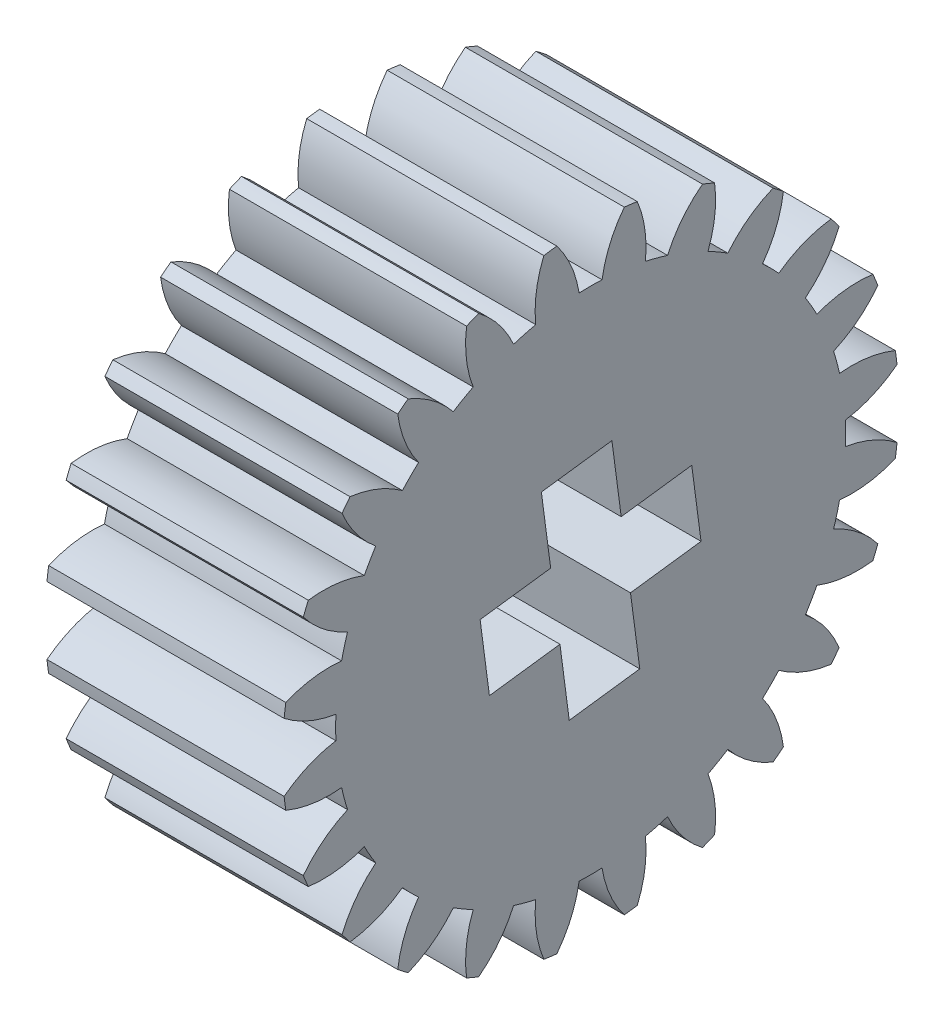
SolidWorks part; units mm, degrees
ref_plane "Plane1" through (0, 0, 0) normal (0, 0, 1) x (1, 0, 0)
ref_plane "Plane2" through (0, 0, 0) normal (0, 1, 0) x (1, 0, 0)
ref_plane "Plane3" through (0, 0, 0) normal (1, 0, 0) x (0, 0, -1)
other "Configuration Table"
sketch "HoldingSke" plane through (0, 0, 0) normal (0, 1, 0) x (1, 0, 0)
  line L0 (0, 0) -> (0.9135, -0.4067)
  line L1 (-15, 0) -> (100, 0) construction
  line L2 (0, 0) -> (-2.1039, 2.3779)
  line L3 (0, 0) -> (-11.863, 4.5341)
  line L4 (0, 0) -> (7.8894, 3.5126)
  line L5 (0, 0) -> (-46.8476, -17.4728)
  line L6 (0, 0) -> (-8.2896, -5.593)
  line L7 (-2.1039, 2.3779) -> (8.6586, 51.2059)
  line L8 (-76.2, 54.61) -> (-76.1, 54.61)
  line L9 (-71.009, 38.7566) -> (-53.1078, 45.2721)
  line L10 (-76.2, 71.12) -> (104.1128, 71.12)
  line L11 (0, 0) -> (-10, 0)
  line L12 (-76.2, 101.6) -> (-76.162, 101.6)
  line L13 (24.9733, 27.94) -> (52.9518, 28.4284)
  line L14 (24.9733, 27.94) -> (24.9743, 27.94)
  line L15 (24.9733, 27.94) -> (100.4006, 29.5858)
  line L16 (-63.627, -1) -> (-12.827, -1)
  circle A0 centre (0, 0) radius 0.5
  circle A1 centre (0, 0) radius 10.749
  circle A2 centre (0, 0) radius 37.5
  circle A3 centre (0, 0) radius 0.5
  dimension "MHD" = 21.498
  dimension "Hub_dia" = 75
  dimension "Bore" = 1
  dimension "MBD" = 1
  dimension "Num_teeth" = 24
  dimension "Pitch" = 1
  dimension "Overall_len" = 50
  dimension "Show_teeth" = 24
  dimension "Thickness" = 10
  dimension "OAL" = 50.0001
  dimension "T_dim" = 0.1
  dimension "Ap" = 20
  dimension "H" = 19.05
  dimension "Pitch_radius" = 180.3128
  dimension "Width" = 10
  dimension "Backlash" = 0.038
  dimension "Addendum_fac" = 1
  dimension "Dedendum_fac" = 1.25
  dimension "Clearance_fac" = 0.25
  dimension "Dedendum_add" = 0.001
  dimension "Module" = 1
sketch "BasProSke" plane through (0, 0, 0) normal (0, 1, 0) x (1, 0, 0)
  line L0 (-10, 0) -> (60, 0) construction
  line L1 (0, 0) -> (0, 13)
  line L2 (0, 0) -> (10, 0)
  line L3 (10, 0) -> (10, 13)
  line L4 (10, 13) -> (0, 13)
  dimension "Thickness" = 10
  dimension "Diameter" = 26
revolve "Base-Revolve" add sketch "BasProSke" angle 360 about L0
sketch "TooCutSke" plane through (0, 0, 0) normal (1, 0, 0) x (0, 0, -1)
  line L1 (0, 0) -> (0, 107) construction
  line L2 (0, 0) -> (-0.8513, 11.9698) construction
  line L3 (0, 0) -> (-3.127, 23.752) construction
  line L4 (-0.8513, 11.9698) -> (-1.5635, 11.876) construction
  arc A0 (0.4834, 10.7381) -> (-0.4834, 10.7381) centre (0, 0) ccw
  arc A1 (1.4409, 12.9455) -> (-1.4409, 12.9455) centre (0, 0) ccw
  circle A2 centre (0, 0) radius 12 construction
  circle A3 centre (0, 0) radius 11.2763 construction
  arc A4 (-0.4834, 10.7381) -> (-1.4409, 12.9455) centre (-5.2252, 9.9926) ccw
  arc A5 (1.4409, 12.9455) -> (0.4834, 10.7381) centre (5.2252, 9.9926) ccw
  dimension "Root_dia" = 21.498
  dimension "Overcut_dia" = 26.0508
  dimension "Pitch_dia" = 24
  dimension "Base_dia" = 22.5526
  dimension "Flank_rad" = 4.8
  dimension "Half_ang" = 7.5
  dimension "Half_CT" = 0.7183
extrude "ToothCut" cut sketch "TooCutSke" along normal through all
fillet "Breaks" [suppressed] radius 0.02
fillet "RootFillets" [suppressed] radius 0.251
pattern_circular "TeethCuts" count 24 every 15 about axis through (-10, 0, 0) along (1, 0, 0) of "ToothCut", "RootFillets", "Breaks"
sketch "HubNeaOneSke" plane through (0, 0, 0) normal (-1, 0, 0) x (0, 0, 1)
  circle A0 centre (0, 0) radius 10.749
  dimension "Diameter" = 21.498
extrude "HubNearOne" [suppressed] add sketch "HubNeaOneSke" along normal blind 40.0001
sketch "HubNeaBotSke" plane through (0, 0, 0) normal (-1, 0, 0) x (0, 0, 1)
  circle A0 centre (0, 0) radius 10.749
  dimension "Diameter" = 21.498
extrude "HubNearBoth" [suppressed] add sketch "HubNeaBotSke" along normal blind 20
ref_plane "FarPln" through (10, 0, 0) normal (1, 0, 0) x (0, 0, -1)
sketch "HubFarSke" plane through (10, 0, 0) normal (1, 0, 0) x (0, 0, -1)
  circle A0 centre (0, 0) radius 10.749
  dimension "Diameter" = 21.498
extrude "HubFar" [suppressed] add sketch "HubFarSke" along normal blind 20
sketch "BorSke" plane through (0, 0, 0) normal (1, 0, 0) x (0, 0, -1)
  circle A0 centre (0, 0) radius 0.5
  dimension "Diameter" = 1
extrude "Bore" cut sketch "BorSke" along normal mid plane 100.0001
sketch "KeySke" plane through (0, 0, 0) normal (1, 0, 0) x (0, 0, -1)
  line L0 (-0.05, 0) -> (-0.05, 0.6)
  line L1 (-0.05, 0.6) -> (0.05, 0.6)
  line L2 (0.05, 0.6) -> (0.05, 0)
  line L3 (0, 0) -> (0, 34) construction
  line L4 (-0.05, 0) -> (0.05, 0)
  dimension "Offset" = 0.6
  dimension "Width" = 0.1
extrude "Keyway" [suppressed] cut sketch "KeySke" along normal mid plane 100.0001
pattern_circular "Keyway2" [suppressed] count 2 every 90 about axis through (-10, 0, 0) along (1, 0, 0)
sketch "Sketch1" plane through (10, 0, 0) normal (1, 0, 0) x (0, 0, -1)
  line L0 (1.6968, -12.8888) -> (-1.6968, 12.8888) construction
  line L1 (-12.8888, -1.6968) -> (12.8888, 1.6968) construction
  line L2 (1.683, -1.2914) -> (4.6573, -0.8998)
  line L3 (-4.2657, -2.0745) -> (-1.2914, -1.683)
  line L4 (-4.2657, -2.0745) -> (-4.6573, 0.8998)
  line L5 (-4.6573, 0.8998) -> (-1.683, 1.2914)
  line L6 (4.6573, -0.8998) -> (4.2657, 2.0745)
  line L7 (2.0745, -4.2657) -> (-0.8998, -4.6573)
  line L8 (2.0745, -4.2657) -> (1.683, -1.2914)
  line L9 (0.8998, 4.6573) -> (-2.0745, 4.2657)
  line L10 (-0.8998, -4.6573) -> (-1.2914, -1.683)
  line L11 (1.2914, 1.683) -> (0.8998, 4.6573)
  line L12 (1.2914, 1.683) -> (4.2657, 2.0745)
  line L13 (-1.683, 1.2914) -> (-2.0745, 4.2657)
  arc A4 (12.9219, 1.4227) -> (12.8498, 1.9702) centre (0, 0) ccw construction
  arc A5 (-12.9219, -1.4227) -> (-12.8498, -1.9702) centre (0, 0) ccw construction
  arc A6 (1.4227, -12.9219) -> (1.9702, -12.8498) centre (0, 0) ccw construction
  arc A7 (-1.4227, 12.9219) -> (-1.9702, 12.8498) centre (0, 0) ccw construction
  point P2 (12.8888, 1.6968)
  point P6 (-12.8888, -1.6968)
  point P12 (1.6968, -12.8888)
  point P16 (0, 0)
  point P25 (-1.6968, 12.8888)
  dimension "D1" = 9
extrude "Cut-Extrude1" cut sketch "Sketch1" against normal through all
equation "' \"Module@HoldingSke\" = 6.35"
equation "' \"Num_teeth@HoldingSke\" = 12"
equation "' \"Ap@HoldingSke\" =  20"
equation "' \"Ap@HoldingSke\" = 20"
equation "' \"Width@HoldingSke\" = 0.5 * 25.4"
equation "' \"Hub_dia@HoldingSke\"= 1 * 25.4"
equation "' \"Hub_dia@HoldingSke\" = 1 * 25.4"
equation "' \"Overall_len@HoldingSke\" = 1.0 * 25.4"
equation "' \"Bore@HoldingSke\" = 0.75 * 25.4"
equation "' \"T_dim@HoldingSke\" = 0.1 * 25.4"
equation "' \"Width@KeySke\" = 0.25 * 25.4"
equation "' \"Show_teeth@HoldingSke\" = 13"
equation "' \"Backlash@HoldingSke\" = 0.009 * 25.4"
equation "' \"Addendum_fac@HoldingSke\" = 1.0"
equation "' \"Dedendum_fac@HoldingSke\" = 1.25"
equation "' \"Dedendum_add@HoldingSke\" = 0.00005 * 25.4"
equation "' \"Clearance_fac@HoldingSke\" = 0.25"
equation "\"Pitch@HoldingSke\" = 1 / \"Module@HoldingSke\""
equation "\"Overcut_dia@TooCutSke\" = (\"Num_teeth@HoldingSke\" + 2 * \"Addendum_fac@HoldingSke\") / \"Pitch@HoldingSke\" + 0.002 * 25.4"
equation "\"Pitch_dia@TooCutSke\" = \"Num_teeth@HoldingSke\" / \"Pitch@HoldingSke\""
equation "\"Base_dia@TooCutSke\" = \"Num_teeth@HoldingSke\" / \"Pitch@HoldingSke\" * cos((\"Ap@HoldingSke\"  * 3.14159265 / 180))"
equation "\"Root_dia@TooCutSke\" = (\"Num_teeth@HoldingSke\" + 2) / \"Pitch@HoldingSke\" - 2 * (\"Addendum_fac@HoldingSke\" + \"Dedendum_fac@HoldingSke\") / \"Pitch@HoldingSke\" - \"Dedendum_add@HoldingSke\" * 2"
equation "\"Half_ang@TooCutSke\" = 180 / \"Num_teeth@HoldingSke\""
equation "\"Half_CT@TooCutSke\" = \"Num_teeth@HoldingSke\" / \"Pitch@HoldingSke\" * sin((3.14159265 / 2 / \"Num_teeth@HoldingSke\")) / 2 - 7 * \"Backlash@HoldingSke\" / 4"
equation "\"Flank_rad@TooCutSke\" = \"Num_teeth@HoldingSke\" / \"Pitch@HoldingSke\" / 5"
equation "\"Radius@RootFillets\" = \"Clearance_fac@HoldingSke\" / \"Pitch@HoldingSke\" + \"Dedendum_add@HoldingSke\""
equation "\"Break_rad@Breaks\" = 0.02 / \"Pitch@HoldingSke\""
equation "\"Thickness@HoldingSke\" = \"Width@HoldingSke\""
equation "\"OAL@HoldingSke\" = \"Thickness@HoldingSke\""
equation "\"MHD@HoldingSke\" = (\"Num_teeth@HoldingSke\" + 2) / \"Pitch@HoldingSke\" - 2 * (\"Addendum_fac@HoldingSke\" + \"Dedendum_fac@HoldingSke\")  / \"Pitch@HoldingSke\" - \"Dedendum_add@HoldingSke\" * 2"
equation "\"MBD@HoldingSke\" = (\"Num_teeth@HoldingSke\" + 2) / \"Pitch@HoldingSke\" - 2 * (\"Addendum_fac@HoldingSke\" + \"Dedendum_fac@HoldingSke\")  / \"Pitch@HoldingSke\" - \"Dedendum_add@HoldingSke\" * 2 - 0.002 * 25.4"
equation "\"MHD@HoldingSke\" = ((sgn( \"MHD@HoldingSke\" - \"Hub_dia@HoldingSke\" )-1)*( \"MHD@HoldingSke\" - \"Hub_dia@HoldingSke\" ))/-2+ \"Hub_dia@HoldingSke\""
equation "\"MBD@HoldingSke\" = ((sgn( \"MBD@HoldingSke\" - \"Bore@HoldingSke\" )-1)*( \"MBD@HoldingSke\" - \"Bore@HoldingSke\" ))/-2+ \"Bore@HoldingSke\""
equation "\"OAL@HoldingSke\" = ((sgn( \"OAL@HoldingSke\" - \"Overall_len@HoldingSke\" )+1)*( \"OAL@HoldingSke\" - \"Overall_len@HoldingSke\" ))/2 + \"Overall_len@HoldingSke\" + 0.000002 * 25.4"
equation "\"Num_teeth@TeethCuts\" = int( \"Show_teeth@HoldingSke\" ) + 1"
equation "\"Num_teeth@TeethCuts\" = ((sgn( \"Num_teeth@TeethCuts\" - \"Num_teeth@HoldingSke\" )-1)*( \"Num_teeth@TeethCuts\" - \"Num_teeth@HoldingSke\" ))/-2+ \"Num_teeth@HoldingSke\""
equation "\"Num_teeth@TeethCuts\" = ((sgn( \"Num_teeth@TeethCuts\" - 2.0)+1)*( \"Num_teeth@TeethCuts\" - 2.0))/2 +2.0"
equation "\"Angle@TeethCuts\" = 360.0 / \"Num_teeth@HoldingSke\""
equation "\"Diameter@BasProSke\" = (\"Num_teeth@HoldingSke\" + 2 * \"Addendum_fac@HoldingSke\") / \"Pitch@HoldingSke\""
equation "\"Thickness@BasProSke\"  = \"Thickness@HoldingSke\""
equation "' \"Fillet_rad@BasProSke\" =  \"Thickness@HoldingSke\" * 0.05"
equation "' \"Fillet_rad@BasProSke\" = \"Thickness@HoldingSke\" * 0.05"
equation "\"MHD@HoldingSke\" = ((sgn( \"MHD@HoldingSke\" - \"Root_dia@TooCutSke\" )-1)*( \"MHD@HoldingSke\" - \"Root_dia@TooCutSke\" ))/-2+ \"Root_dia@TooCutSke\""
equation "\"Diameter@HubNeaOneSke\" = \"MHD@HoldingSke\""
equation "\"Length@HubNearOne\" = \"OAL@HoldingSke\" - \"Thickness@BasProSke\""
equation "\"Diameter@HubNeaBotSke\" = \"MHD@HoldingSke\""
equation "\"Length@HubNearBoth\" = ( \"OAL@HoldingSke\" - \"Thickness@BasProSke\" ) / 2.0"
equation "\"Thickness@FarPln\" = \"Thickness@BasProSke\""
equation "\"Diameter@HubFarSke\" = \"MHD@HoldingSke\""
equation "\"Length@HubFar\" = ( \"OAL@HoldingSke\" - \"Thickness@BasProSke\" ) / 2.0"
equation "\"Diameter@BorSke\" = \"MBD@HoldingSke\""
equation "\"D1@Bore\" = \"OAL@HoldingSke\" * 2.0"
equation "\"D1@Keyway\" = \"OAL@HoldingSke\" * 2.0"
equation "\"Offset@KeySke\" = \"T_dim@HoldingSke\" + \"MBD@HoldingSke\" / 2.0"
